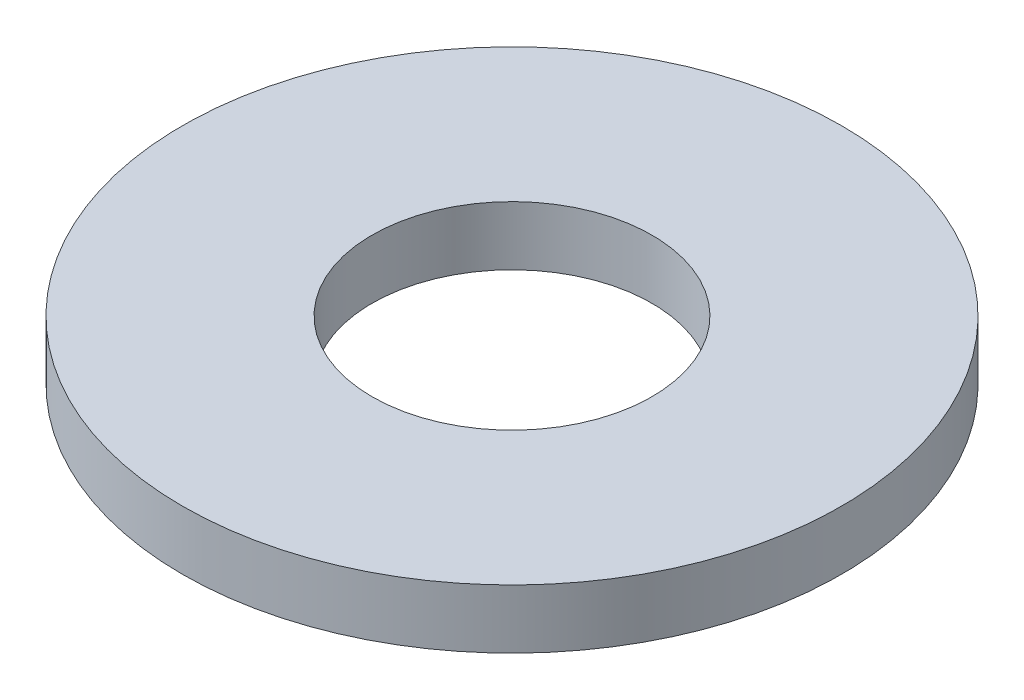
SolidWorks part; units mm, degrees
material "Alloy Steel"
ref_plane "front" through (0, 0, 0) normal (0, 0, 1) x (1, 0, 0)
ref_plane "top" through (0, 0, 0) normal (0, 1, 0) x (1, 0, 0)
ref_plane "side" through (0, 0, 0) normal (1, 0, 0) x (0, 0, -1)
other "Configuration Table"
sketch "Sketch1" plane through (0, 0, 0) normal (0, 1, 0) x (1, 0, 0)
  circle A0 centre (0, 0) radius 6.7437
  circle A1 centre (0, 0) radius 15.875
  dimension "D1" = 31.75
  dimension "D2" = 13.4874
extrude "Base-Extrude" add sketch "Sketch1" along normal blind 2.8448
